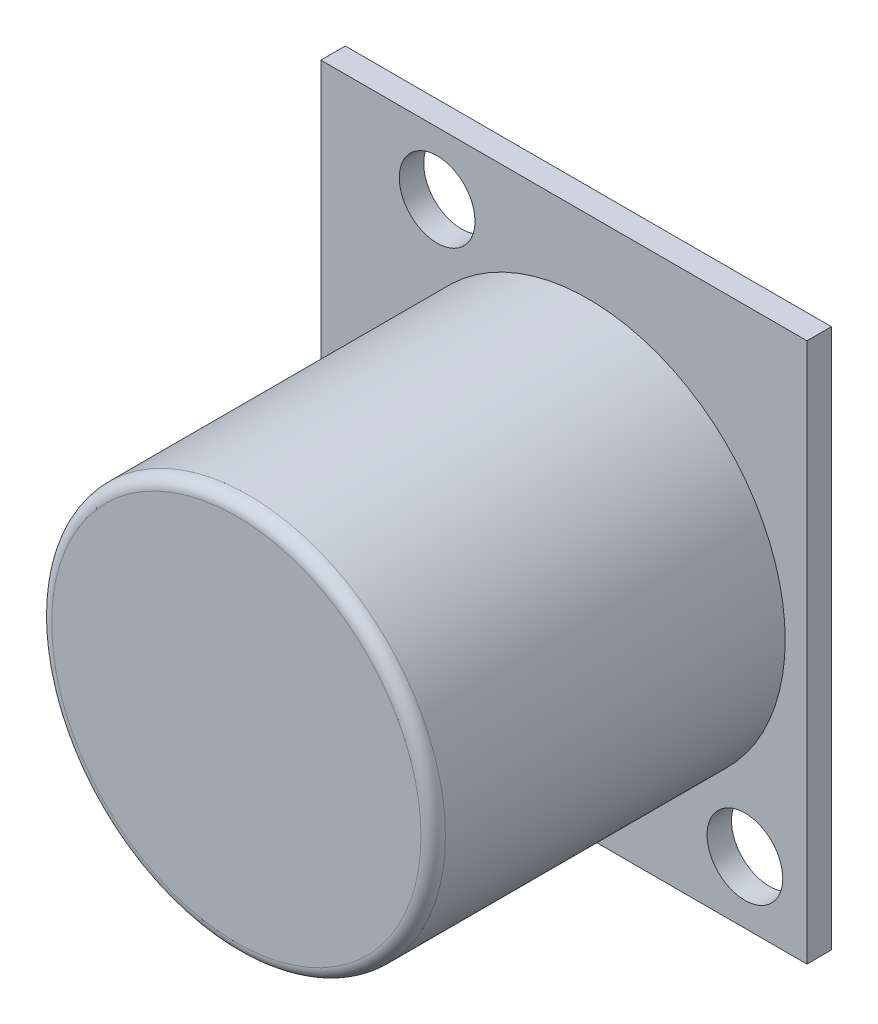
SolidWorks part; units mm, degrees
ref_plane "Front Plane" through (0, 0, 0) normal (0, 0, 1) x (1, 0, 0)
ref_plane "Top Plane" through (0, 0, 0) normal (0, 1, 0) x (1, 0, 0)
ref_plane "Right Plane" through (0, 0, 0) normal (1, 0, 0) x (0, 0, -1)
sketch "Sketch1" plane through (0, 0, 0) normal (0, 0, 1) x (1, 0, 0)
  line L1 (0, 0) -> (19.9, 0)
  line L2 (0, 0) -> (0, -22.1)
  line L3 (0, -22.1) -> (19.9, -22.1)
  line L4 (19.9, 0) -> (19.9, -22.1)
  dimension "D1" = 19.9
  dimension "D2" = 22.1
extrude "Extrude1" add sketch "Sketch1" along normal blind 1
sketch "Sketch2" plane through (0, 0, 1) normal (0, 0, 1) x (1, 0, 0)
  line L0 (19.9, 0) -> (0, 0) construction
  line L1 (0, -22.1) -> (19.9, -22.1) construction
  line L2 (19.9, -22.1) -> (19.9, 0) construction
  circle A0 centre (4.76, -2.56) radius 1.55
  circle A1 centre (17.36, -19.56) radius 1.55
  dimension "D3" = 3.1
  dimension "D4" = 3.1
  dimension "D1" = 2.56
  dimension "D2" = 2.54
  dimension "D5" = 2.54
  dimension "D6" = 12.6
extrude "Extrude2" cut sketch "Sketch2" against normal blind 1
sketch "Sketch3" plane through (0, 0, 1) normal (0, 0, 1) x (1, 0, 0)
  line L0 (19.9, -22.1) -> (19.9, 0) construction
  line L1 (19.9, 0) -> (0, 0) construction
  circle A0 centre (10.95, -11.05) radius 8.06
  dimension "D1" = 16.12
  dimension "D2" = 8.95
  dimension "D3" = 11.05
extrude "Extrude3" add sketch "Sketch3" along normal blind 14.41
fillet "Fillet1" radius 0.5 1 edges at (19.01, -11.05, 15.41)
